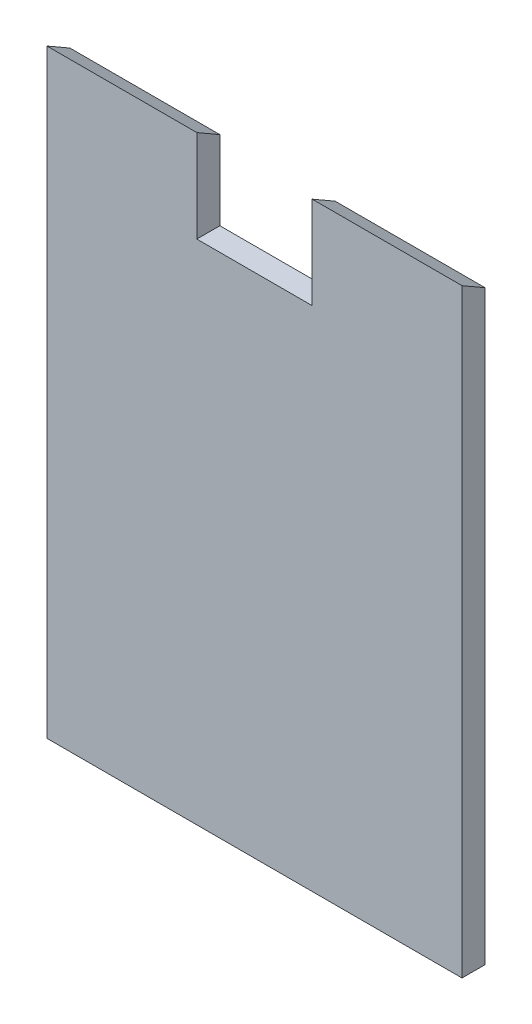
SolidWorks part; units mm, degrees
ref_plane "Front Plane" through (0, 0, 0) normal (0, 0, 1) x (1, 0, 0)
ref_plane "Top Plane" through (0, 0, 0) normal (0, 1, 0) x (1, 0, 0)
ref_plane "Right Plane" through (0, 0, 0) normal (1, 0, 0) x (0, 0, -1)
sketch "Sketch1" plane through (0, 0, 0) normal (0, 0, 1) x (1, 0, 0)
  line L0 (0, -262.711) -> (0, 262.711) construction
  line L1 (114.3, -165.1) -> (-114.3, -165.1)
  line L2 (114.3, -165.1) -> (114.3, 165.1)
  line L3 (114.3, 165.1) -> (31.75, 165.1)
  line L4 (-114.3, -165.1) -> (-114.3, 165.1)
  line L5 (114.3, -165.1) -> (-114.3, 165.1) construction
  line L6 (114.3, 165.1) -> (-114.3, -165.1) construction
  line L7 (-31.75, 114.3) -> (31.75, 114.3)
  line L8 (-31.75, 114.3) -> (-31.75, 165.1)
  line L9 (31.75, 114.3) -> (31.75, 165.1)
  line L10 (-31.75, 165.1) -> (-114.3, 165.1)
  point P0 (0, 0)
  point P9 (0, 0)
  point P12 (0, 114.3)
  dimension "D1" = 330.2
  dimension "D2" = 228.6
  dimension "D3" = 63.5
  dimension "D4" = 50.8
extrude "Boss-Extrude1" add sketch "Sketch1" along normal mid plane 12.7
sketch "Sketch2" plane through (0, 0, 0) normal (1, 0, 0) x (0, 0, -1)
  line L0 (0, -209.8682) -> (0, 209.8682) construction
  line L1 (-6.35, 165.1) -> (6.35, 165.1)
  line L2 (-6.35, 165.1) -> (6.35, 165.1) construction
  line L3 (6.35, -165.1) -> (6.35, 165.1) construction
  line L4 (6.35, 165.1) -> (6.35, 157.7677)
  line L5 (-6.35, 165.1) -> (6.35, 157.7677)
  point P4 (0, 0)
  dimension "D1" = 30
extrude "Cut-Extrude1" cut sketch "Sketch2" against normal mid plane 254
